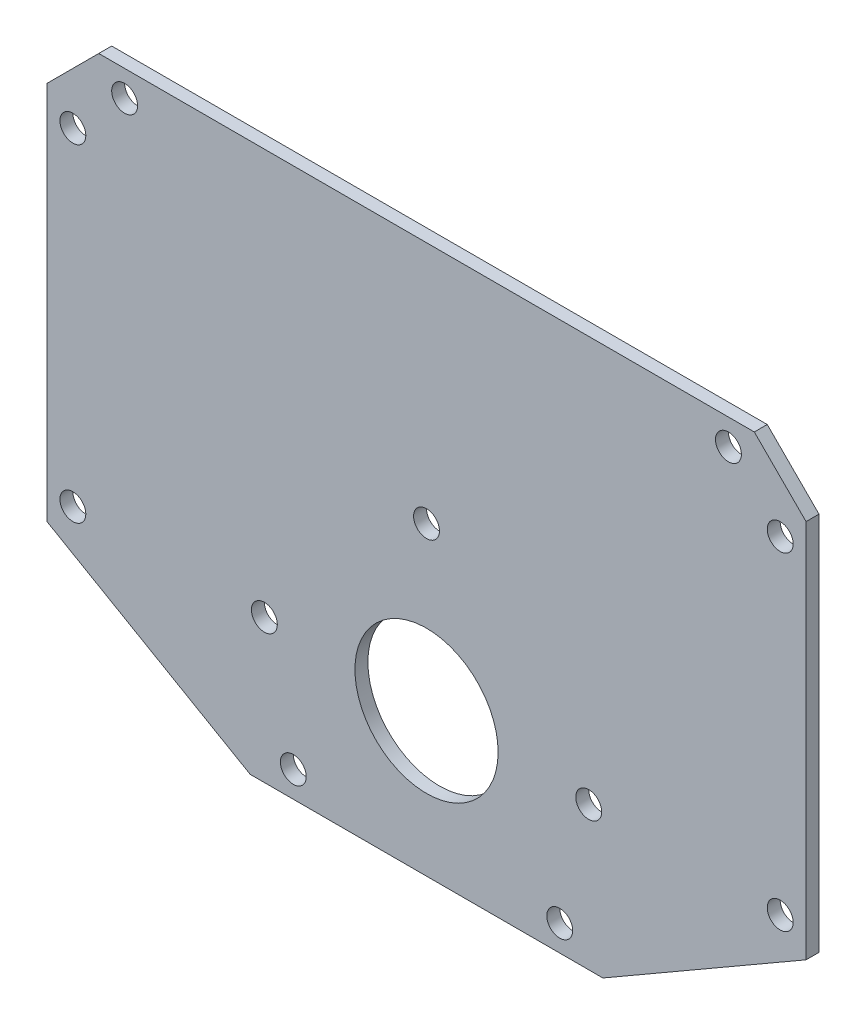
SolidWorks part; units mm, degrees
material "Thornel Mat VMA"
ref_plane "前视基准面" through (0, 0, 0) normal (0, 0, 1) x (1, 0, 0)
ref_plane "上视基准面" through (0, 0, 0) normal (0, 1, 0) x (1, 0, 0)
ref_plane "右视基准面" through (0, 0, 0) normal (1, 0, 0) x (0, 0, -1)
other "Configuration Table"
sketch "草图1" plane through (0, 0, 0) normal (0, 0, 1) x (1, 0, 0)
  line L0 (-44, -22) -> (-20.4441, -35.6)
  line L2 (-44, 22) -> (-44, -22)
  line L3 (-44, -22) -> (44, -22) construction
  line L4 (44, 22) -> (44, -22)
  line L5 (-44, 22) -> (44, -22) construction
  line L6 (-44, -22) -> (44, 22) construction
  line L7 (44, -22) -> (20.4441, -35.6)
  line L8 (-20.4441, -35.6) -> (20.4441, -35.6)
  line L9 (-44, 22) -> (-38, 28)
  line L10 (44, 22) -> (38, 28)
  line L11 (-38, 28) -> (38, 28)
  circle A0 centre (-41, 19) radius 1.5
  circle A1 centre (-41, -19) radius 1.5
  circle A2 centre (41, 19) radius 1.5
  circle A3 centre (41, -19) radius 1.5
  point P0 (0, 0)
  point P20 (0, -19)
  dimension "D7" = 3
  dimension "D8" = 3
  dimension "D1" = 88
  dimension "D2" = 44
  dimension "D3" = 30
  dimension "D4" = 30
  dimension "D5" = 13.6
  dimension "D6" = 3
  dimension "D9" = 3
extrude "凸台-拉伸1" add sketch "草图1" along normal blind 1.5
sketch "草图2" plane through (0, 0, 1.5) normal (0, 0, 1) x (1, 0, 0)
  line L0 (-20.4441, -35.6) -> (20.4441, -35.6) construction
  line L1 (38, 28) -> (-38, 28) construction
  circle A0 centre (0, -0.2) radius 1.5
  circle A1 centre (-18.8, -19) radius 1.5
  circle A2 centre (18.8, -19) radius 1.5
  circle A3 centre (0, -19) radius 8.3
  circle A4 centre (-15.4441, -32.6) radius 1.5
  circle A5 centre (15.4441, -32.6) radius 1.5
  circle A6 centre (-35, 25) radius 1.5
  circle A7 centre (35, 25) radius 1.5
  point P26 (0, 0)
  point P28 (-52.194, 47.1623)
  dimension "D1" = 18.8
  dimension "D4" = 5
  dimension "D8" = 3
  dimension "D2" = 18.8
  dimension "D3" = 18.8
  dimension "D5" = 3
  dimension "D6" = 5
  dimension "D7" = 3
  dimension "D9" = 3
  dimension "D10" = 3
  dimension "D11" = 3
extrude "切除-拉伸1" cut sketch "草图2" against normal blind 10
